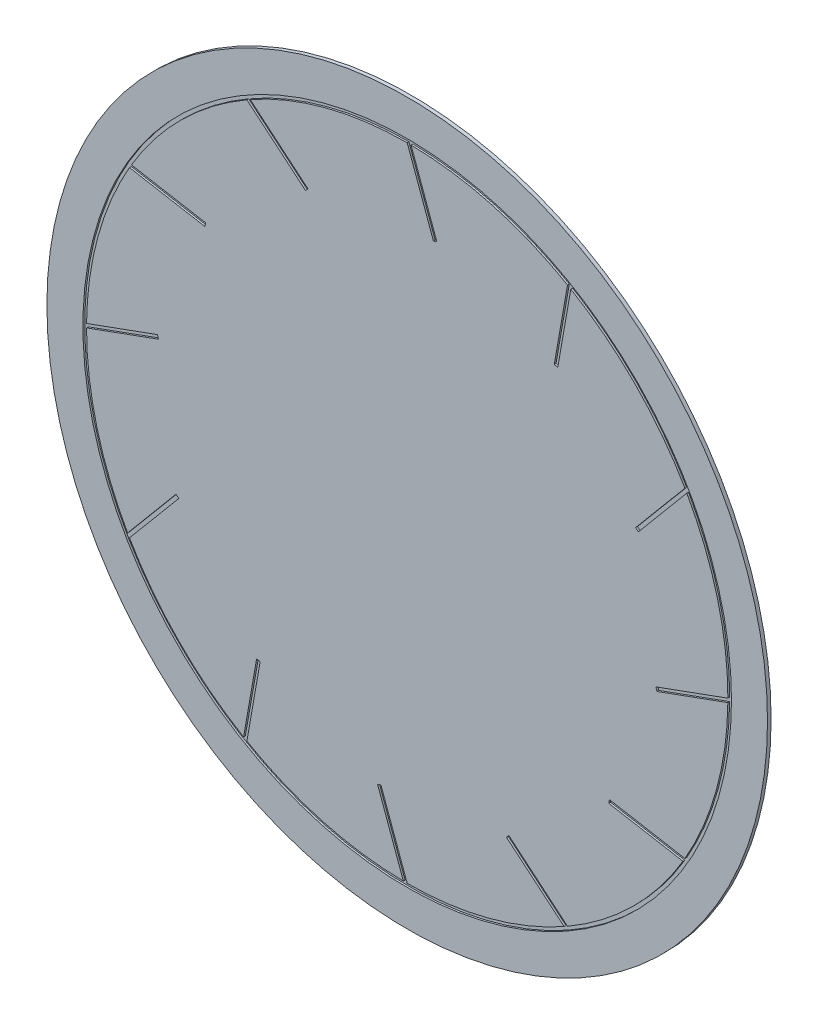
SolidWorks part; units mm, degrees
ref_plane "Front Plane" through (0, 0, 0) normal (0, 0, 1) x (1, 0, 0)
ref_plane "Top Plane" through (0, 0, 0) normal (0, 1, 0) x (1, 0, 0)
ref_plane "Right Plane" through (0, 0, 0) normal (1, 0, 0) x (0, 0, -1)
sketch "Sketch1" plane through (0, 0, 0) normal (0, 0, 1) x (1, 0, 0)
  circle A0 centre (0, 0) radius 254
  dimension "D1" = 508
extrude "Boss-Extrude1" add sketch "Sketch1" along normal blind 2.54
sketch "Sketch2" plane through (0, 0, 2.54) normal (0, 0, 1) x (1, 0, 0)
  circle A0 centre (0, 0) radius 228.6
  circle A1 centre (0, 0) radius 226.06
  dimension "D1" = 457.2
  dimension "D2" = 452.12
extrude "Cut-Extrude1" cut sketch "Sketch2" against normal blind 1.27
sketch "Sketch4" plane through (0, 0, 2.54) normal (0, 0, 1) x (1, 0, 0)
  line L0 (0, 0) -> (-286.1423, 0) construction
  line L1 (-226.06, 0) -> (-175.26, 18.4897)
  line L2 (-175.26, 18.4897) -> (-176.1287, 20.8765)
  line L3 (-176.1287, 20.8765) -> (-226.0438, 2.7089)
  line L4 (-195.7737, 113.03) -> (-142.5348, 103.6425)
  line L5 (-142.5348, 103.6425) -> (-142.0937, 106.144)
  line L6 (-142.0937, 106.144) -> (-194.4052, 115.3679)
  line L7 (-113.03, 195.7737) -> (-71.6175, 161.0245)
  line L8 (-71.6175, 161.0245) -> (-69.9848, 162.9702)
  line L9 (-69.9848, 162.9702) -> (-110.6759, 197.1141)
  line L10 (0, 226.06) -> (18.4897, 175.26)
  line L11 (18.4897, 175.26) -> (20.8765, 176.1287)
  line L12 (20.8765, 176.1287) -> (2.7089, 226.0438)
  line L13 (113.03, 195.7737) -> (103.6425, 142.5348)
  line L14 (103.6425, 142.5348) -> (106.144, 142.0937)
  line L15 (106.144, 142.0937) -> (115.3679, 194.4052)
  line L16 (195.7737, 113.03) -> (161.0245, 71.6175)
  line L17 (161.0245, 71.6175) -> (162.9702, 69.9848)
  line L18 (162.9702, 69.9848) -> (197.1141, 110.6759)
  line L19 (226.06, 0) -> (175.26, -18.4897)
  line L20 (175.26, -18.4897) -> (176.1287, -20.8765)
  line L21 (176.1287, -20.8765) -> (226.0438, -2.7089)
  line L22 (195.7737, -113.03) -> (142.5348, -103.6425)
  line L23 (142.5348, -103.6425) -> (142.0937, -106.144)
  line L24 (142.0937, -106.144) -> (194.4052, -115.3679)
  line L25 (113.03, -195.7737) -> (71.6175, -161.0245)
  line L26 (71.6175, -161.0245) -> (69.9848, -162.9702)
  line L27 (69.9848, -162.9702) -> (110.6759, -197.1141)
  line L28 (0, -226.06) -> (-18.4897, -175.26)
  line L29 (-18.4897, -175.26) -> (-20.8765, -176.1287)
  line L30 (-20.8765, -176.1287) -> (-2.7089, -226.0438)
  line L31 (-113.03, -195.7737) -> (-103.6425, -142.5348)
  line L32 (-103.6425, -142.5348) -> (-106.144, -142.0937)
  line L33 (-106.144, -142.0937) -> (-115.3679, -194.4052)
  line L34 (-195.7737, -113.03) -> (-161.0245, -71.6175)
  line L35 (-161.0245, -71.6175) -> (-162.9702, -69.9848)
  line L36 (-162.9702, -69.9848) -> (-197.1141, -110.6759)
  circle A0 centre (0, 0) radius 226.06 construction
  arc A1 (-226.0438, 2.7089) -> (-226.06, 0) centre (0, 0) ccw
  arc A2 (-194.4052, 115.3679) -> (-195.7737, 113.03) centre (0, 0) ccw
  arc A3 (-110.6759, 197.1141) -> (-113.03, 195.7737) centre (0, 0) ccw
  arc A4 (2.7089, 226.0438) -> (0, 226.06) centre (0, 0) ccw
  arc A5 (115.3679, 194.4052) -> (113.03, 195.7737) centre (0, 0) ccw
  arc A6 (197.1141, 110.6759) -> (195.7737, 113.03) centre (0, 0) ccw
  arc A7 (226.0438, -2.7089) -> (226.06, 0) centre (0, 0) ccw
  arc A8 (194.4052, -115.3679) -> (195.7737, -113.03) centre (0, 0) ccw
  arc A9 (110.6759, -197.1141) -> (113.03, -195.7737) centre (0, 0) ccw
  arc A10 (-2.7089, -226.0438) -> (0, -226.06) centre (0, 0) ccw
  arc A11 (-115.3679, -194.4052) -> (-113.03, -195.7737) centre (0, 0) ccw
  arc A12 (-197.1141, -110.6759) -> (-195.7737, -113.03) centre (0, 0) ccw
  dimension "D1" = 2.54
  dimension "D3" = 50.8
extrude "Cut-Extrude2" cut sketch "Sketch4" against normal blind 1.27
